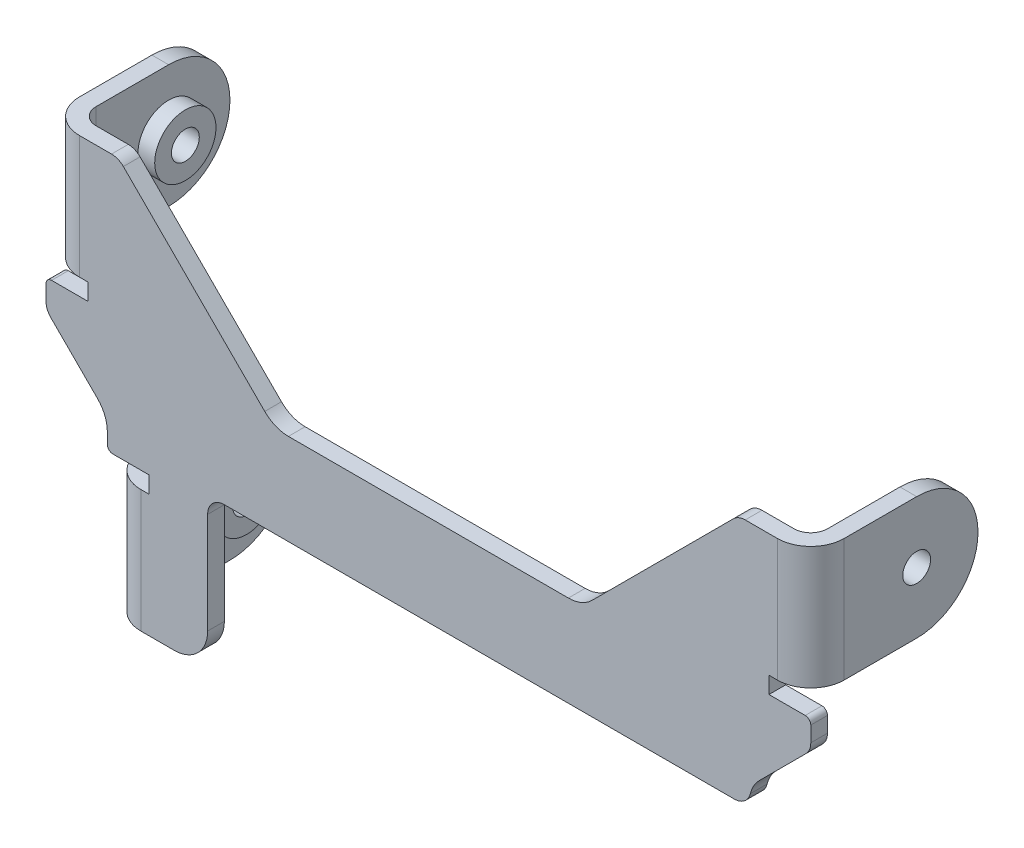
SolidWorks part; units mm, degrees
ref_plane "前视基准面" through (0, 0, 0) normal (0, 0, 1) x (1, 0, 0)
ref_plane "上视基准面" through (0, 0, 0) normal (0, 1, 0) x (1, 0, 0)
ref_plane "右视基准面" through (0, 0, 0) normal (1, 0, 0) x (0, 0, -1)
sketch "草图1" plane through (0, 0, 0) normal (0, 0, 1) x (1, 0, 0)
  line L0 (6.75, 24.7574) -> (6.75, 37)
  line L1 (6.75, 37) -> (1.25, 37)
  line L2 (1.25, 37) -> (1.25, 24.7574)
  line L3 (1.25, 24.7574) -> (6.75, 24.7574)
extrude "凸台-拉伸1" add sketch "草图1" against normal blind 1.5
sketch "草图2" plane through (6.75, 0, 0) normal (1, 0, 0) x (0, 0, -1)
  line L0 (1.5, 37) -> (1.5, 12.2574)
  line L1 (1.5, 12.2574) -> (0, 12.2574)
  line L2 (0, 12.2574) -> (0, 37)
  line L3 (0, 37) -> (1.5, 37)
extrude "凸台-拉伸2" add sketch "草图2" along normal blind 55.6
sketch "草图3" plane through (6.75, 0, 0) normal (-1, 0, 0) x (0, 0, 1)
  line L0 (0, 12.2574) -> (-1.5, 12.2574)
  line L1 (-1.5, 12.2574) -> (-1.5, 23.2574)
  line L2 (-1.5, 23.2574) -> (0, 23.2574)
  line L3 (0, 23.2574) -> (0, 12.2574)
extrude "凸台-拉伸3" add sketch "草图3" along normal blind 2.25
sketch "草图4" plane through (0, 37, 0) normal (0, 1, 0) x (-1, 0, 0)
  line L0 (1, -1.5) -> (-62.35, -1.5)
  line L1 (-62.35, -1.5) -> (-62.35, 0)
  line L2 (-62.35, 0) -> (1, 0)
  line L3 (1, 0) -> (1, -1.5)
extrude "凸台-拉伸4" add sketch "草图4" along normal blind 11
sketch "草图5" plane through (-1, 0, 0) normal (-1, 0, 0) x (0, 0, 1)
  line L0 (-9.5, 48) -> (0, 48)
  line L1 (0, 48) -> (0, 37)
  line L2 (0, 37) -> (-9.5, 37)
  arc A0 (-9.5, 37) -> (-9.5, 48) centre (-9.5, 42.5) cw
extrude "凸台-拉伸5" add sketch "草图5" along normal blind 1.5
sketch "草图6" plane through (4.5, 0, 0) normal (-1, 0, 0) x (0, 0, 1)
  line L0 (-9.5, 23.2574) -> (0, 23.2574)
  line L1 (0, 23.2574) -> (0, 12.2574)
  line L2 (0, 12.2574) -> (-9.5, 12.2574)
  arc A0 (-9.5, 12.2574) -> (-9.5, 23.2574) centre (-9.5, 17.7574) cw
extrude "凸台-拉伸6" add sketch "草图6" along normal blind 1.5
sketch "草图7" plane through (62.35, 0, 0) normal (1, 0, 0) x (0, 0, -1)
  line L0 (0, 48) -> (1.5, 48)
  line L1 (1.5, 48) -> (1.5, 37)
  line L2 (1.5, 37) -> (0, 37)
  line L3 (0, 37) -> (0, 48)
extrude "凸台-拉伸7" add sketch "草图7" along normal blind 2.25
sketch "草图8" plane through (64.6, 0, 0) normal (1, 0, 0) x (0, 0, -1)
  line L0 (9.5, 37) -> (0, 37)
  line L1 (0, 37) -> (0, 48)
  line L2 (0, 48) -> (9.5, 48)
  arc A0 (9.5, 48) -> (9.5, 37) centre (9.5, 42.5) cw
extrude "凸台-拉伸8" add sketch "草图8" along normal blind 1.5
sketch "草图9" plane through (62.35, 0, 0) normal (1, 0, 0) x (0, 0, -1)
  line L0 (1.5, 35.5) -> (1.5, 12.2574)
  line L1 (1.5, 12.2574) -> (0, 12.2574)
  line L2 (0, 12.2574) -> (0, 35.5)
  line L3 (0, 35.5) -> (1.5, 35.5)
extrude "凸台-拉伸9" add sketch "草图9" along normal blind 3.75
sketch "草图10" plane through (1.25, 0, 0) normal (-1, 0, 0) x (0, 0, 1)
  line L0 (0, 35.5) -> (0, 24.7574)
  line L1 (0, 24.7574) -> (-1.5, 24.7574)
  line L2 (-1.5, 24.7574) -> (-1.5, 35.5)
  line L3 (-1.5, 35.5) -> (0, 35.5)
extrude "凸台-拉伸10" add sketch "草图10" along normal blind 3.75
sketch "草图11" plane through (0, 0, -1.5) normal (0, 0, -1) x (-1, 0, 0)
  line L0 (2.5, 24.7574) -> (2.5, 33)
  line L1 (2.5, 33) -> (-3, 27.5)
  line L2 (-3, 27.5) -> (-3, 24.7574)
  line L3 (-3, 24.7574) -> (2.5, 24.7574)
extrude "切除-拉伸1" cut sketch "草图11" against normal through all
sketch "草图12" plane through (0, 0, -1.5) normal (0, 0, -1) x (-1, 0, 0)
  line L0 (-12, 25.8229) -> (-66.1, 25.8229)
  line L1 (-66.1, 25.8229) -> (-66.1, 12.2574)
  line L2 (-66.1, 12.2574) -> (-12, 12.2574)
  line L3 (-12, 12.2574) -> (-12, 25.8229)
extrude "切除-拉伸2" cut sketch "草图12" against normal through all
sketch "草图13" plane through (0, 0, -1.5) normal (0, 0, -1) x (-1, 0, 0)
  line L0 (-61.4787, 28.3787) -> (-66.1, 33)
  line L1 (-66.1, 33) -> (-66.1, 25.8229)
  line L2 (-66.1, 25.8229) -> (-60.6316, 25.8229)
  arc A0 (-60.6316, 25.8229) -> (-61.4787, 28.3787) centre (-63.6, 26.2574) ccw
extrude "切除-拉伸3" cut sketch "草图13" against normal through all
sketch "草图14" plane through (0, 0, -1.5) normal (0, 0, -1) x (-1, 0, 0)
  line L0 (-59.6, 48) -> (-45.6, 34)
  line L1 (-45.6, 34) -> (-18, 34)
  line L2 (-18, 34) -> (-4, 48)
  line L3 (-4, 48) -> (-59.6, 48)
extrude "切除-拉伸4" cut sketch "草图14" against normal through all
ref_plane "基准面1" through (0, 0, -9.5) normal (0, 0, -1) x (-1, 0, 0)
sketch "草图15" plane through (0, 0, -9.5) normal (0, 0, -1) x (-1, 0, 0)
  line L0 (-6, 20.5074) -> (-6, 17.7574)
  line L1 (-6, 17.7574) -> (-4.5, 17.7574)
  line L2 (-4.5, 17.7574) -> (-4.5, 20.5074)
  line L3 (-4.5, 20.5074) -> (-6, 20.5074)
  line L4 (-6, 17.7574) -> (-4.5, 17.7574) construction
revolve "旋转1" add sketch "草图15" angle 360 about L4
sketch "草图16" plane through (0, 0, -9.5) normal (0, 0, -1) x (-1, 0, 0)
  line L0 (-0.5, 45.25) -> (-0.5, 42.5)
  line L1 (-0.5, 42.5) -> (1, 42.5)
  line L2 (1, 42.5) -> (1, 45.25)
  line L3 (1, 45.25) -> (-0.5, 45.25)
  line L4 (-0.5, 42.5) -> (1, 42.5) construction
revolve "旋转2" add sketch "草图16" angle 360 about L4
ref_plane "基准面2" through (0, 0, -9.5) normal (0, 0, 1) x (1, 0, 0)
sketch "草图17" plane through (0, 0, -9.5) normal (0, 0, 1) x (1, 0, 0)
  line L0 (63.1, 45.25) -> (63.1, 42.5)
  line L1 (63.1, 42.5) -> (64.6, 42.5)
  line L2 (64.6, 42.5) -> (64.6, 45.25)
  line L3 (64.6, 45.25) -> (63.1, 45.25)
  line L4 (63.1, 42.5) -> (64.6, 42.5) construction
revolve "旋转3" add sketch "草图17" angle 360 about L4
hole_wizard "Ø2.5 (2.5) 直径孔1" positions "草图19" profile "草图18" hole size "Ø2.5" standard "ANSI Metric"
sketch "草图19" plane through (3, 0, 0) normal (-1, 0, 0) x (0, 0, 1)
  point P0 (-9.5, 17.7574)
sketch "草图18" plane through (3, 17.7574, -9.5) normal (0, 1, 0) x (0, 0, 1)
  line L0 (0, 0) -> (0, 63.1)
  line L1 (0, 63.1) -> (1.25, 63.1)
  line L2 (1.25, 63.1) -> (1.25, 0)
  line L5 (1.25, 0) -> (0, 0)
  line L11 (0, -6.35) -> (0, 107.95) construction
  dimension "通孔孔直径" = 2.5
  dimension "通孔孔深度" = 63.1
hole_wizard "Ø2.5 (2.5) 直径孔2" positions "草图21" profile "草图20" hole size "Ø2.5" standard "ANSI Metric"
sketch "草图21" plane through (-2.5, 0, 0) normal (-1, 0, 0) x (0, 0, 1)
  point P0 (-9.5, 42.5)
sketch "草图20" plane through (-2.5, 42.5, -9.5) normal (0, 1, 0) x (0, 0, 1)
  line L0 (0, 0) -> (0, 3)
  line L1 (0, 3) -> (1.25, 3)
  line L2 (1.25, 3) -> (1.25, 0)
  line L5 (1.25, 0) -> (0, 0)
  line L11 (0, -6.35) -> (0, 107.95) construction
  dimension "通孔孔直径" = 2.5
  dimension "通孔孔深度" = 3
hole_wizard "Ø2.5 (2.5) 直径孔3" positions "草图23" profile "草图22" hole size "Ø2.5" standard "ANSI Metric"
sketch "草图23" plane through (66.1, 0, 0) normal (1, 0, 0) x (0, 0, -1)
  point P0 (9.5, 42.5)
sketch "草图22" plane through (66.1, 42.5, -9.5) normal (0, 1, 0) x (0, 0, -1)
  line L0 (0, 0) -> (0, 68.6)
  line L1 (0, 68.6) -> (1.25, 68.6)
  line L2 (1.25, 68.6) -> (1.25, 0)
  line L5 (1.25, 0) -> (0, 0)
  line L11 (0, -6.35) -> (0, 107.95) construction
  dimension "通孔孔直径" = 2.5
  dimension "通孔孔深度" = 68.6
fillet "圆角1" radius 0.5 3 edges at (66.1, 35.5, -0.75) (3, 24.7574, -0.75) (-2.5, 35.5, -0.75)
fillet "圆角2" radius 1.5 9 edges at (-2.5, 33, -0.75) (60.6316, 25.8229, -0.75) (-1, 42.5, -1.5) (4.5, 17.7574, -1.5) (12, 25.8229, -0.75) (64.6, 42.5, -1.5) (66.1, 33, -0.75) (4, 48, -0.75) (59.6, 48, -0.75)
fillet "圆角3" radius 3 7 edges at (66.1, 42.5, 0) (18, 34, -0.75) (45.6, 34, -0.75) (3, 27.5, -0.75) (12, 12.2574, -0.75) (3, 17.7574, 0) (-2.5, 42.5, 0)
